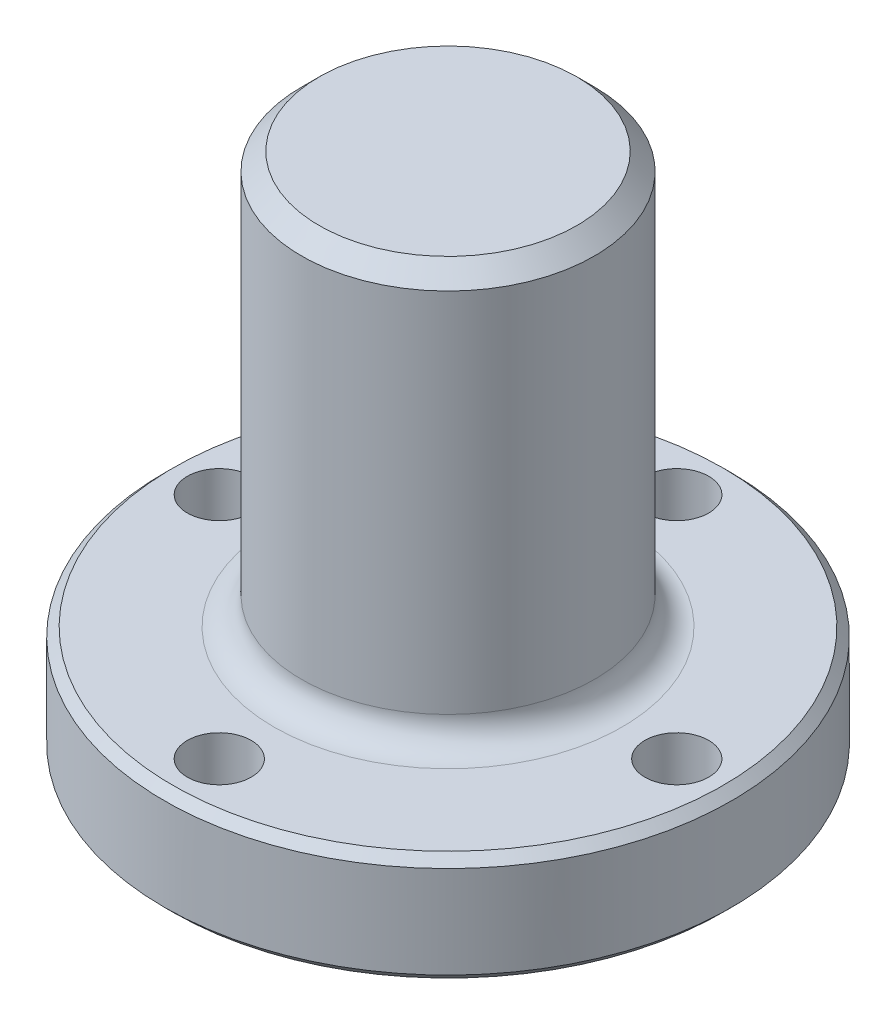
SolidWorks part; units mm, degrees
ref_plane "Front Plane" through (0, 0, 0) normal (1, 0, 0) x (0, 1, 0)
ref_plane "Top Plane" through (0, 0, 0) normal (0, 0, 1) x (0, 1, 0)
ref_plane "Right Plane" through (0, 0, 0) normal (0, 1, 0) x (-1, 0, 0)
sketch "Sketch1" plane through (0, 0, 0) normal (0, 0, 1) x (0, 1, 0)
  line L0 (-25.0317, 0) -> (-25.0317, 8.7122)
  line L1 (-25.0317, 8.7122) -> (-20.2057, 8.7122)
  line L2 (-20.2057, 8.7122) -> (-20.2057, 24.6126)
  line L3 (-20.2057, 24.6126) -> (-10.6807, 24.6126)
  line L4 (-10.6807, 24.6126) -> (-10.6807, 12.7)
  line L5 (-10.6807, 12.7) -> (25.0317, 12.7)
  line L6 (25.0317, 12.7) -> (25.0317, 0)
  line L7 (25.0317, 0) -> (-25.0317, 0)
  line L8 (-50.4317, 0) -> (50.4317, 0) construction
  point P10 (0, 0)
  dimension "D1" = 35.7124
  dimension "D2" = 45.2374
  dimension "D3" = 50.0634
  dimension "D4" = 11.9126
  dimension "D5" = 15.9004
  dimension "D6" = 24.6126
revolve "Revolve1" add sketch "Sketch1" angle 360 about L8
sketch "Sketch2" plane through (0, 0, 0) normal (0, 1, 0) x (-1, 0, 0)
  circle A0 centre (19.8374, 0) radius 2.7686
  circle A1 centre (0, 19.8374) radius 2.7686
  circle A2 centre (-19.8374, 0) radius 2.7686
  circle A3 centre (0, -19.8374) radius 2.7686
  point P8 (0, 0)
  dimension "D1" = 5.5372
  dimension "D2" = 5.5372
  dimension "D3" = 5.5372
  dimension "D4" = 5.5372
  dimension "D5" = 19.8374
  dimension "D6" = 19.8374
  dimension "D7" = 39.6748
  dimension "D8" = 19.8374
  dimension "D9" = 19.8374
  dimension "D10" = 39.6748
extrude "Cut-Extrude2" cut sketch "Sketch2" along normal blind 20.2057 from offset 20.2057
fillet "Fillet1" radius 2.3876 1 edges at (0, -10.6807, -12.7)
chamfer "Chamfer1" distance 0.762 angle 45 2 edges at (0, -10.6807, -24.6126) (0, -20.2057, -24.6126)
chamfer "Chamfer2" distance 1.524 angle 45 1 edges at (0, 25.0317, -12.7)
